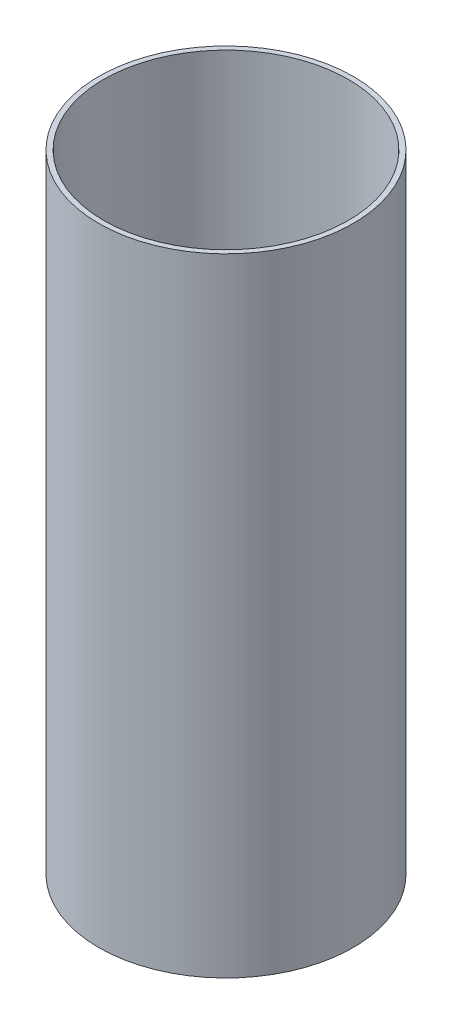
SolidWorks part; units mm, degrees
material "Hexcel AS4C (3000 Filaments)"
ref_plane "Front Plane" through (0, 0, 0) normal (0, 0, 1) x (1, 0, 0)
ref_plane "Top Plane" through (0, 0, 0) normal (0, 1, 0) x (1, 0, 0)
ref_plane "Right Plane" through (0, 0, 0) normal (1, 0, 0) x (0, 0, -1)
sketch "Sketch1" plane through (0, 0, 0) normal (0, 1, 0) x (1, 0, 0)
  circle A0 centre (0, 0) radius 49.53
  circle A1 centre (0, 0) radius 51.562
  dimension "D1" = 99.06
  dimension "D2" = 2.032
extrude "Boss-Extrude1" add sketch "Sketch1" along normal blind 254
equation "\"CF_OD_A\"= 4.015in"
equation "\"CF_ID_A\"= 3.904in"
equation "\"KF_ID_A\"= 4.015in ' Kevlar airframe ID"
equation "\"CF_OD_C\"= 3.894in ' VERIFY Coupler OD"
equation "\"CF_ID_C\"= 3.783in ' VERIFY Coupler ID"
equation "\"KF_WALL\"= 0.0625in"
equation "\"AF_01\"=10in"
equation "\"AF_02\"=16in"
equation "\"AF_03\"=in"
equation "\"B_CF_OD\"=6.17in"
equation "\"B_CF_ID\"=6in"
equation "\"B_CF_WT\"=0.085in"
equation "\"B_Fin_Root\"=18in"
equation "\"Al_WALL\"=0.08in"
equation "\"AL_ID_A\"=3.9in"
equation "\"D1@Sketch1\"=\"AL_ID_A\""
equation "\"D2@Sketch1\"=\"Al_WALL\""
equation "\"D1@Boss-Extrude1\"=\"AF_01\""
